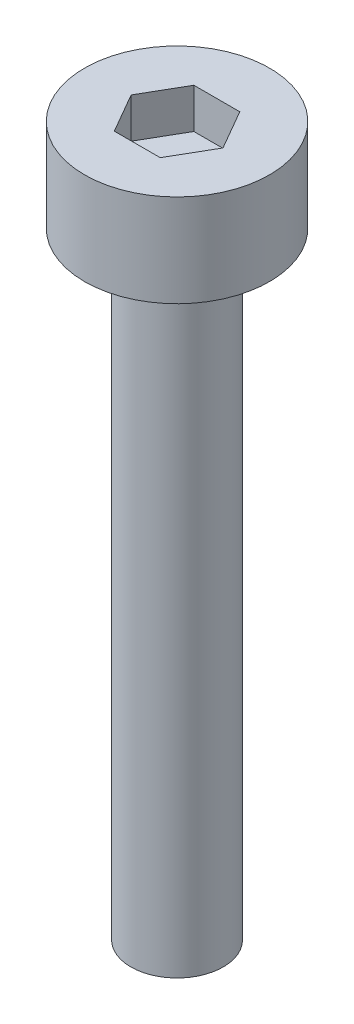
SolidWorks part; units mm, degrees
ref_plane "Front Plane" through (0, 0, 0) normal (0, 0, 1) x (1, 0, 0)
ref_plane "Top Plane" through (0, 0, 0) normal (0, 1, 0) x (1, 0, 0)
ref_plane "Right Plane" through (0, 0, 0) normal (1, 0, 0) x (0, 0, -1)
sketch "Sketch1" plane through (0, 0, 0) normal (0, 1, 0) x (1, 0, 0)
  circle A0 centre (0, 0) radius 1.5
  dimension "D1" = 3
extrude "ScrewShaft" add sketch "Sketch1" along normal blind 20
sketch "Sketch2" plane through (0, 20, 0) normal (0, 1, 0) x (1, 0, 0)
  circle A0 centre (0, 0) radius 3
  dimension "D1" = 6
extrude "Boss-Extrude2" add sketch "Sketch2" along normal blind 3
sketch "Sketch3" plane through (0, 23, 0) normal (0, 1, 0) x (1, 0, 0)
  line L0 (0, 0) -> (0, 1.29) construction
  line L1 (1.4896, 0) -> (0.7448, 1.29)
  line L2 (0.7448, 1.29) -> (-0.7448, 1.29)
  line L3 (-0.7448, 1.29) -> (-1.4896, 0)
  line L4 (-1.4896, 0) -> (-0.7448, -1.29)
  line L5 (-0.7448, -1.29) -> (0.7448, -1.29)
  line L6 (0.7448, -1.29) -> (1.4896, 0)
  circle A0 centre (0, 0) radius 1.29 construction
  dimension "D1" = 2.58
extrude "Cut-Extrude1" cut sketch "Sketch3" against normal blind 1.3
equation "\"X-ROD-SPACING\"=45"
equation "\"Y-ROD-SPACING\"=75"
equation "\"Z-ROD-SPACING\"=17.5"
equation "\"Y-BED-OFFSET\"=2"
equation "\"Y-BED-ROD-INSET\"=3.5"
equation "\"T-SLOT-NUT-FILLET-RADIUS\"=0.5"
equation "\"T-SLOT-SCREW-SHAFT-RADIUS\"=1.55"
equation "\"T-SLOT-SCREW-SHAFT-CUTOUT-LENGTH\"=11.0"
equation "\"T-SLOT-NUT-DEPTH\"=3.5"
equation "\"T-SLOT-NUT-WIDTH\"=2.85"
equation "\"T-SLOT-NUT-END-DISTANCE\"=8"
equation "\"ACRYLIC-THICKNESS\"=10"
equation "\"ACRYLIC-THICKNESS2\"=4.5"
equation "\"ACRYLIC-TAB-CUTOUT-SIZE\"=\"ACRYLIC-THICKNESS\"+\"ACRYLIC-TAB-TOLERANCE\"*2"
equation "\"ACRYLIC-TAB-WIDTH\"=\"ACRYLIC-THICKNESS\""
equation "\"ACRYLIC-M3-HOLE\"=2.9"
equation "\"SMOOTHROD-CAP-SCREW-DISTANCE\"=20"
equation "\"FRAME-WIDTH-INNER\"=370"
equation "\"NEMA17-HOLE-SPACING\"=31"
equation "\"NEMA17-CENTRAL-CUTOUT\"=22.5"
equation "\"Z-BRACKET-REACH\"=55"
equation "\"TOP-BRACKET-SPACING\"=40"
equation "\"SMOOTHROD-X-LENGTH\"=350"
equation "\"SMOOTHROD-Y-LENGTH\"=350"
equation "\"SMOOTHROD-Z-LENGTH\"=350"
equation "\"SMOOTHROD-TIGHTENING-HEADROOM\"=.25"
equation "\"LEADSCREW-Z-LENGTH\"=300"
equation "\"SCREW-LENGTH-FRAME\"=\"ACRYLIC-THICKNESS\" + 10"
equation "\"SCREW-HEAD-RADIUS\"=6"
equation "\"PRINTED-X-SMOOTHROD-DIAMETER\"=8.4"
equation "\"PRINTED-X-SMOOTHROD-CUTOUT\"=10"
equation "\"PRINTED-X-BASE-HEIGHT\"=10"
equation "\"PRINTED-LM8UU-CUTOUT-SIZE\"=15.5"
equation "\"PRINTED-LM8UU-CUTOUT-LENGTH\"=24.5"
equation "\"PRINTED-X-IDLER-HEIGHT\"=16"
equation "\"PSU-MOUNTING-WIDTH\"=95"
equation "\"PSU-MOUNTING-HEIGHT\"=177"
equation "\"D1@ScrewShaft\"=\"SCREW-LENGTH-FRAME\""
equation "\"D1@Sketch2\"=\"SCREW-HEAD-RADIUS\""
